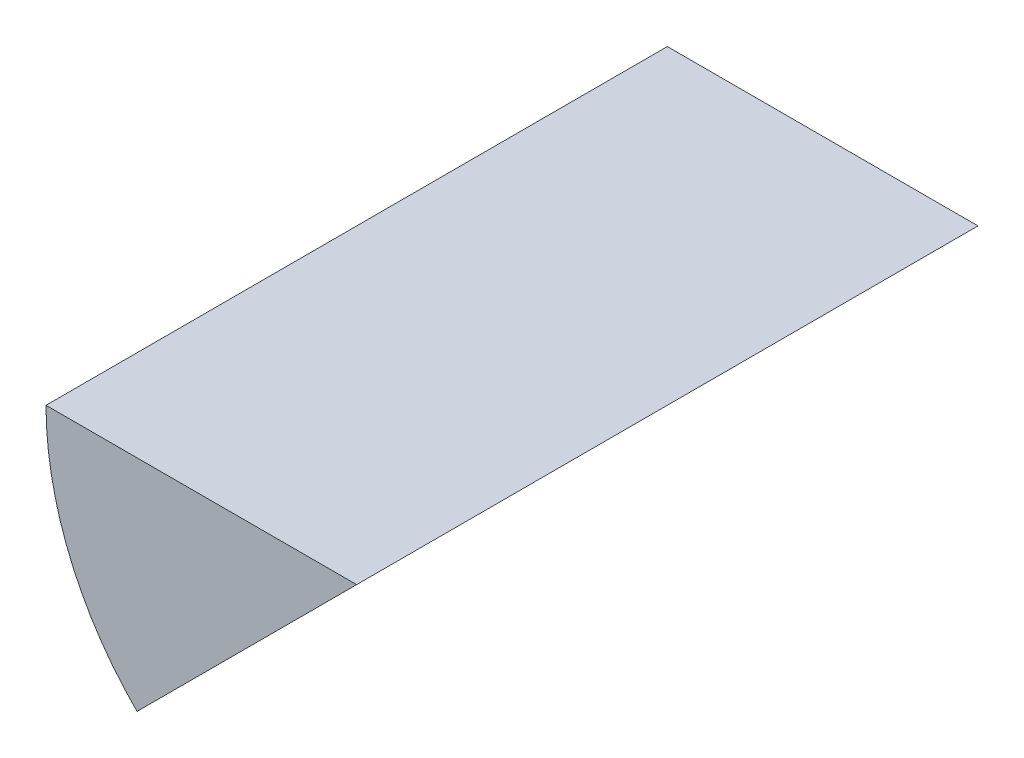
SolidWorks part; units mm, degrees
ref_plane "Alzado" through (0, 0, 0) normal (0, 0, 1) x (1, 0, 0)
ref_plane "Planta" through (0, 0, 0) normal (0, 1, 0) x (1, 0, 0)
ref_plane "Vista lateral" through (0, 0, 0) normal (1, 0, 0) x (0, 0, -1)
sketch "Croquis1" plane through (0, 0, 0) normal (0, 0, 1) x (1, 0, 0)
  line L1 (0, 0) -> (-25, 0)
  line L2 (0, 0) -> (-17.6777, -17.6777)
  arc A0 (-25, 0) -> (-17.6777, -17.6777) centre (0, 0) ccw
  dimension "D1" = 50
extrude "Saliente-Extruir1" add sketch "Croquis1" along normal blind 50
sketch "Croquis2" plane through (0, 0, 0) normal (0, 0, -1) x (-1, 0, 0)
  circle A0 centre (16.1769, -6.2281) radius 5
  dimension "D1" = 10
extrude "Cortar-Extruir1" cut sketch "Croquis2" against normal blind 10 contours A0
